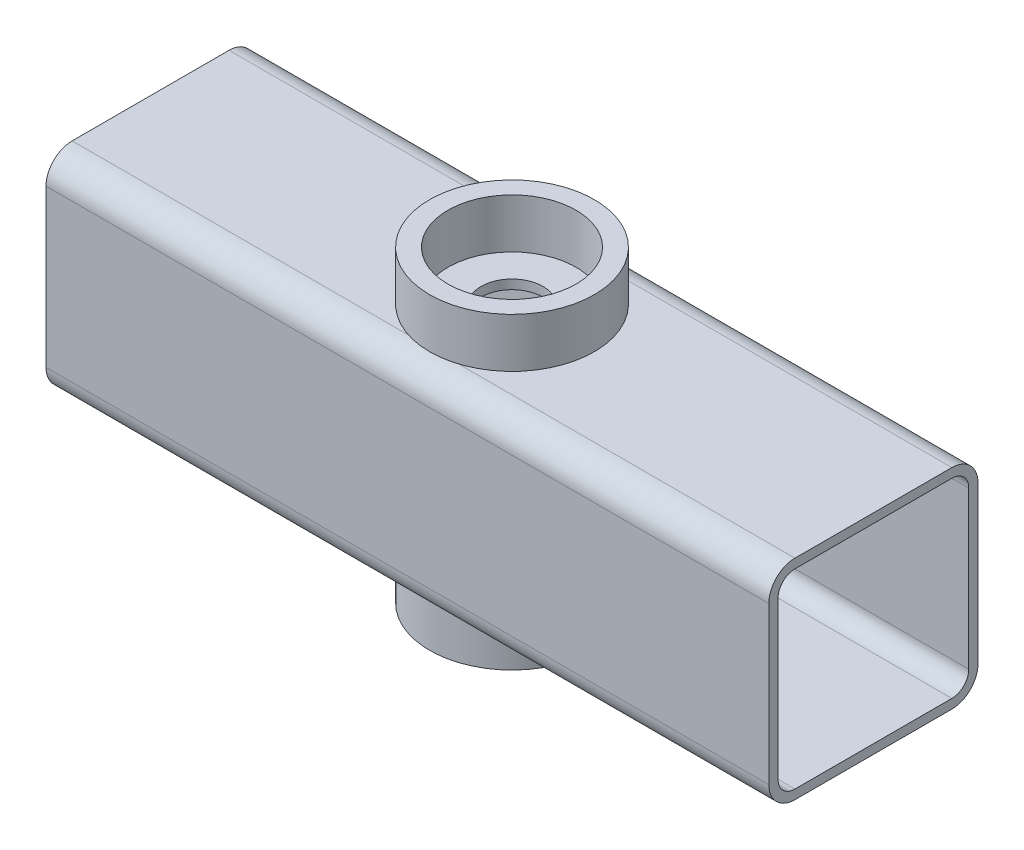
SolidWorks part; units mm, degrees
material "AISI 1020 Acero laminado en frío"
ref_plane "Alzado" through (0, 0, 0) normal (0, 0, 1) x (1, 0, 0)
ref_plane "Planta" through (0, 0, 0) normal (0, 1, 0) x (1, 0, 0)
ref_plane "Vista lateral" through (0, 0, 0) normal (1, 0, 0) x (0, 0, -1)
sketch "Croquis1" plane through (0, 0, 0) normal (0, 0, 1) x (1, 0, 0)
  line L0 (-178.3088, 0) -> (172.6912, 0)
  dimension "D1" = 351
other "Miembro estructural1"
ref_plane "Plano1" through (-178.3088, 0, 0) normal (1, 0, 0) x (0, 1, 0)
sketch "Sketch1" plane through (-178.3088, 0, 0) normal (1, 0, 0) x (0, 1, 0)
  line L0 (-38.1, -46.3) -> (38.1, -46.3)
  line L1 (-46.3, -38.1) -> (-46.3, 38.1)
  line L2 (38.1, 46.3) -> (-38.1, 46.3)
  line L3 (46.3, 38.1) -> (46.3, -38.1)
  line L4 (-38.1, -50.8) -> (38.1, -50.8)
  line L5 (-50.8, -38.1) -> (-50.8, 38.1)
  line L6 (38.1, 50.8) -> (-38.1, 50.8)
  line L7 (50.8, 38.1) -> (50.8, -38.1)
  line L8 (0, 0) -> (46.3, 0) construction
  line L9 (0, 0) -> (0, 46.3) construction
  arc A0 (50.8, 38.1) -> (38.1, 50.8) centre (38.1, 38.1) ccw
  arc A1 (38.1, -50.8) -> (50.8, -38.1) centre (38.1, -38.1) ccw
  arc A2 (-50.8, -38.1) -> (-38.1, -50.8) centre (-38.1, -38.1) ccw
  arc A3 (-38.1, 50.8) -> (-50.8, 38.1) centre (-38.1, 38.1) ccw
  arc A4 (-38.1, 46.3) -> (-46.3, 38.1) centre (-38.1, 38.1) ccw
  arc A5 (46.3, 38.1) -> (38.1, 46.3) centre (38.1, 38.1) ccw
  arc A6 (38.1, -46.3) -> (46.3, -38.1) centre (38.1, -38.1) ccw
  arc A7 (-46.3, -38.1) -> (-38.1, -46.3) centre (-38.1, -38.1) ccw
  point P3 (0, 50.8)
  point P4 (50.8, 0)
  point P5 (0, -50.8)
  point P6 (-50.8, 0)
  point P7 (-50.8, 50.8)
  point P8 (-50.8, -50.8)
  point P33 (0, 0)
  point P35 (50.8, -50.8)
  point P36 (50.8, 50.8)
  point P37 (0, 0)
  dimension "D1" = 12.7
  dimension "Thickness" = 4.5
  dimension "V_leg" = 101.6
hole_wizard "Taladro de margen para M391" positions "Croquis3" profile "Croquis2" hole size "M39" standard "Ansi Metric" end condition through all
sketch "Croquis3" plane through (0, 50.8, 0) normal (0, 1, 0) x (1, 0, 0)
  line L0 (-178.3088, 0) -> (-2.8088, 0) construction
  line L1 (-178.3088, 38.1) -> (-178.3088, -38.1) construction
  line L2 (-2.8088, 0) -> (-2.8088, 38.1) construction
  line L3 (172.6912, 38.1) -> (-178.3088, 38.1) construction
  point P0 (-2.8088, 0)
sketch "Croquis2" plane through (-2.8088, 50.8, 0) normal (1, 0, 0) x (0, 0, 1)
  line L0 (0, 0) -> (0, 101.6)
  line L1 (0, 101.6) -> (15, 101.6)
  line L2 (15, 101.6) -> (15, 0)
  line L5 (15, 0) -> (0, 0)
  line L11 (0, -6.35) -> (0, 107.95) construction
  dimension "Diámetro de taladro hasta el siguiente" = 30
  dimension "Profundidad de taladro hasta el siguiente" = 101.6
sketch "Croquis6" plane through (0, 50.8, 0) normal (0, 1, 0) x (1, 0, 0)
  circle A0 centre (-2.8088, 0) radius 40
extrude "Saliente-Extruir1" add sketch "Croquis6" along normal blind 24 separate body
sketch "Croquis7" plane through (0, 74.8, 0) normal (0, 1, 0) x (1, 0, 0)
  circle A3 centre (-2.8088, 0) radius 31.1
  dimension "D1" = 62.2
extrude "Cortar-Extruir1" cut sketch "Croquis7" against normal blind 30
sketch "Croquis8" plane through (0, -50.8, 0) normal (0, -1, 0) x (-1, 0, 0)
  circle A0 centre (2.8088, 0) radius 40
extrude "Saliente-Extruir2" add sketch "Croquis8" along normal blind 24 separate body
sketch "Croquis9" plane through (0, -74.8, 0) normal (0, -1, 0) x (-1, 0, 0)
  circle A0 centre (2.8088, 0) radius 31.1
  dimension "D1" = 62.2
extrude "Cortar-Extruir2" cut sketch "Croquis9" against normal blind 30
